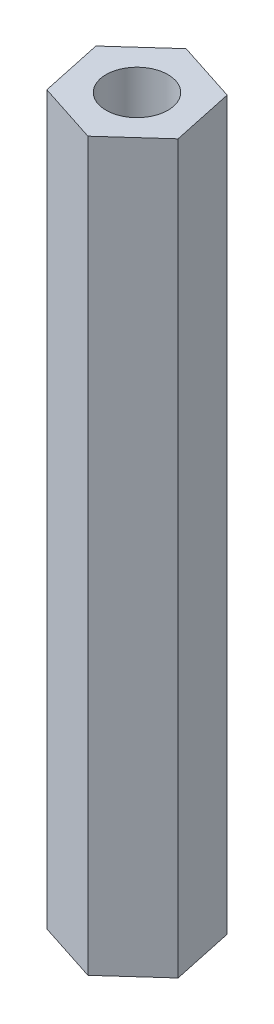
SolidWorks part; units mm, degrees
ref_plane "Plano frontal" through (0, 0, 0) normal (0, 0, 1) x (1, 0, 0)
ref_plane "Plano superior" through (0, 0, 0) normal (0, 1, 0) x (1, 0, 0)
ref_plane "Plano direito" through (0, 0, 0) normal (1, 0, 0) x (0, 0, -1)
sketch "Esboço1" plane through (0, 0, 0) normal (0, 1, 0) x (1, 0, 0)
  line L1 (3.092, -1.001) -> (2.4129, 2.1772)
  line L2 (2.4129, 2.1772) -> (-0.6791, 3.1783)
  line L3 (-0.6791, 3.1783) -> (-3.092, 1.001)
  line L4 (-3.092, 1.001) -> (-2.4129, -2.1772)
  line L5 (-2.4129, -2.1772) -> (0.6791, -3.1783)
  line L6 (0.6791, -3.1783) -> (3.092, -1.001)
  circle A0 centre (0, 0) radius 3.25 construction
extrude "Ressalto-extrusão1" add sketch "Esboço1" along normal blind 37
hole_wizard "Furo roscado para conduíte de M3x0.51" positions "Esboço2" profile "Esboço3" tap size "M3x0.5" standard "Helicoil® Metric"
sketch "Esboço2" plane through (0, 0, 0) normal (0, -1, 0) x (-1, 0, 0)
  point P0 (0, 0)
cosmetic thread "Rosca de furo1" parameters "D1"=10, "D2"=3.716
sketch "Esboço3" plane through (0, 0, 0) normal (1, 0, 0) x (0, 0, -1)
  line L0 (0, 0) -> (0, 10.9464)
  line L1 (0, 10.9464) -> (1.575, 10)
  line L2 (1.575, 10) -> (1.575, 0)
  line L5 (1.575, 0) -> (0, 0)
  line L10 (0, 10.9464) -> (-1.575, 10) construction
  line L11 (0, -6.35) -> (0, 107.95) construction
  dimension "Tap Drill Dia." = 3.15
  dimension "Tap Drill Depth" = 10
  dimension "Drill Angle" = 118
hole_wizard "Furo roscado para conduíte de M3x0.52" positions "Esboço5" profile "Esboço4" tap size "M3x0.5" standard "Helicoil® Metric"
sketch "Esboço5" plane through (0, 37, 0) normal (0, 1, 0) x (1, 0, 0)
  point P3 (0, 0)
sketch "Esboço4" plane through (0, 37, 0) normal (1, 0, 0) x (0, 0, 1)
  line L0 (0, 0) -> (0, 10.9464)
  line L1 (0, 10.9464) -> (1.575, 10)
  line L2 (1.575, 10) -> (1.575, 0)
  line L5 (1.575, 0) -> (0, 0)
  line L10 (0, 10.9464) -> (-1.575, 10) construction
  line L11 (0, -6.35) -> (0, 107.95) construction
  dimension "Tap Drill Dia." = 3.15
  dimension "Tap Drill Depth" = 10
  dimension "Drill Angle" = 118
cosmetic thread "Rosca de furo2" parameters "D1"=10, "D2"=3.716
